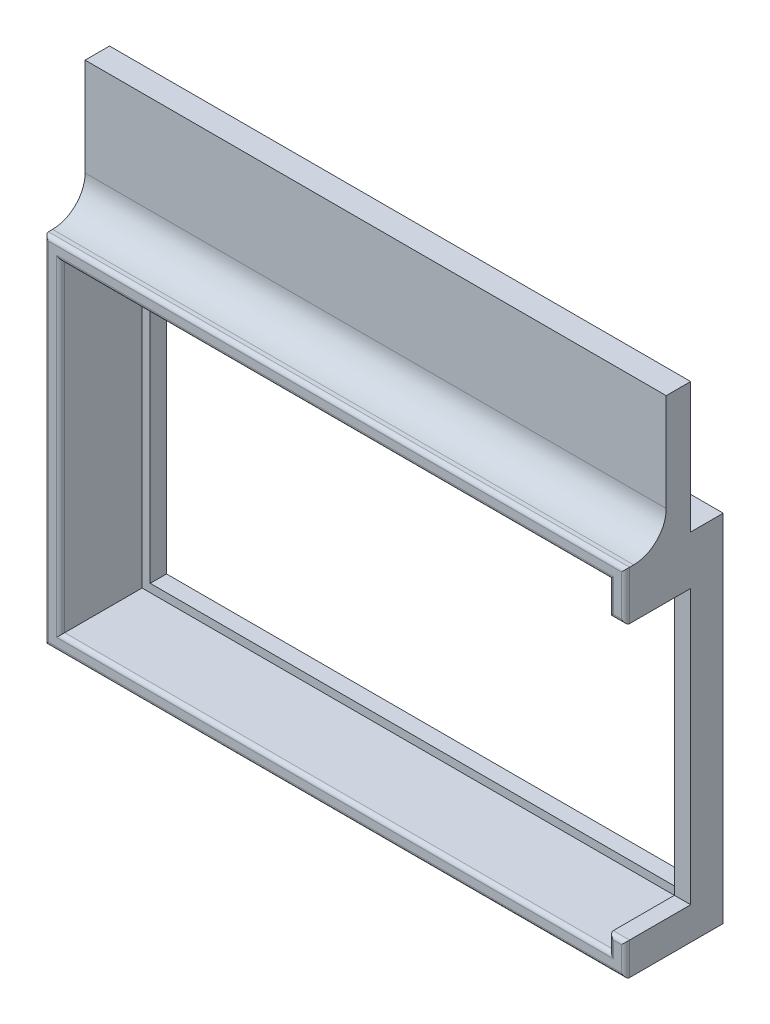
SolidWorks part; units mm, degrees
ref_plane "Plan de face" through (0, 0, 0) normal (0, 0, 1) x (1, 0, 0)
ref_plane "Plan de dessus" through (0, 0, 0) normal (0, 1, 0) x (1, 0, 0)
ref_plane "Plan de droite" through (0, 0, 0) normal (1, 0, 0) x (0, 0, -1)
sketch "Esquisse1" plane through (0, 0, 0) normal (0, 0, 1) x (1, 0, 0)
  line L1 (0, 0) -> (35.68, 0)
  line L2 (0, 0) -> (0, 21.82)
  line L3 (0, 21.82) -> (35.68, 21.82)
  line L4 (35.68, 0) -> (35.68, 21.82)
extrude "Boss.-Extru.1" add sketch "Esquisse1" along normal blind 6
sketch "Esquisse2" plane through (0, 0, 6) normal (0, 0, 1) x (1, 0, 0)
  line L0 (0, 0) -> (35.68, 0) construction
  line L1 (1, 1) -> (34.68, 1)
  line L2 (1, 1) -> (1, 20.82)
  line L3 (1, 20.82) -> (34.68, 20.82)
  line L4 (34.68, 1) -> (34.68, 20.82)
  line L5 (0, 21.82) -> (0, 0) construction
  line L6 (35.68, 21.82) -> (0, 21.82) construction
  line L7 (35.68, 0) -> (35.68, 21.82) construction
  dimension "D1" = 1
  dimension "D2" = 1
  dimension "D3" = 1
  dimension "D4" = 1
extrude "Enlèv. mat.-Extru.1" cut sketch "Esquisse2" against normal blind 5
sketch "Esquisse3" plane through (0, 0, 1) normal (0, 0, 1) x (1, 0, 0)
  line L1 (1.5, 1.5) -> (34.18, 1.5)
  line L2 (1.5, 1.5) -> (1.5, 20.32)
  line L3 (1.5, 20.32) -> (34.18, 20.32)
  line L4 (34.18, 1.5) -> (34.18, 20.32)
  line L5 (1, 1) -> (34.68, 1) construction
  line L6 (1, 20.82) -> (1, 1) construction
  line L7 (34.68, 1) -> (34.68, 20.82) construction
  line L8 (34.68, 20.82) -> (1, 20.82) construction
  dimension "D1" = 0.5
  dimension "D2" = 0.5
  dimension "D3" = 0.5
  dimension "D4" = 0.5
extrude "Enlèv. mat.-Extru.2" cut sketch "Esquisse3" against normal through all
sketch "Esquisse4" plane through (35.68, 0, 0) normal (1, 0, 0) x (0, 0, -1)
  line L0 (-6, 0) -> (-6, 21.82) construction
  line L1 (-6, 18.82) -> (-2, 18.82)
  line L2 (-6, 18.82) -> (-6, 2)
  line L3 (-6, 2) -> (-2, 2)
  line L4 (-2, 18.82) -> (-2, 2)
  line L5 (-6, 0) -> (0, 0) construction
  line L6 (-6, 21.82) -> (0, 21.82) construction
  line L7 (0, 0) -> (0, 21.82) construction
  dimension "D1" = 0
  dimension "D2" = 2
  dimension "D3" = 3
  dimension "D4" = 2
extrude "Enlèv. mat.-Extru.3" cut sketch "Esquisse4" against normal blind 5
sketch "Esquisse6" plane through (0, 0, 6) normal (0, 0, 1) x (1, 0, 0)
  line L0 (0, 21.82) -> (0, 0) construction
  line L1 (0, 21.82) -> (35.68, 21.82)
  line L2 (0, 21.82) -> (0, 29.82)
  line L3 (0, 29.82) -> (35.68, 29.82)
  line L4 (35.68, 21.82) -> (35.68, 29.82)
  line L5 (35.68, 2) -> (35.68, 18.82) construction
  line L6 (35.68, 21.82) -> (0, 21.82) construction
  dimension "D1" = 0
  dimension "D2" = 0
  dimension "D3" = 8
  dimension "D4" = 0
extrude "Boss.-Extru.2" add sketch "Esquisse6" against normal blind 4
sketch "Esquisse7" plane through (0, 0, 6) normal (0, 0, 1) x (1, 0, 0)
  line L0 (35.68, 29.82) -> (0, 29.82) construction
  line L1 (0, 29.82) -> (35.68, 29.82)
  line L2 (0, 29.82) -> (0, 21.82)
  line L3 (0, 21.82) -> (35.68, 21.82)
  line L4 (35.68, 29.82) -> (35.68, 21.82)
  line L5 (0, 29.82) -> (0, 0) construction
  line L6 (35.68, 18.82) -> (35.68, 29.82) construction
  line L8 (34.68, 20.82) -> (1, 20.82) construction
  dimension "D1" = 0
  dimension "D2" = 0
  dimension "D3" = 0
  dimension "D4" = 1
  dimension "D5" = 8
extrude "Enlèv. mat.-Extru.12" cut sketch "Esquisse7" against normal blind 2.5
fillet "Congé2" radius 0.25 12 edges at (35.18, 18.82, 6) (34.68, 19.82, 6) (17.84, 20.82, 6) (1, 10.91, 6) (17.84, 1, 6) (34.68, 1.5, 6) (35.18, 2, 6) (35.68, 1, 6) (17.84, 0, 6) (0, 10.91, 6) (17.84, 21.82, 6) (35.68, 20.32, 6)
fillet "Congé3" radius 2 1 edges at (17.84, 21.82, 3.5)
